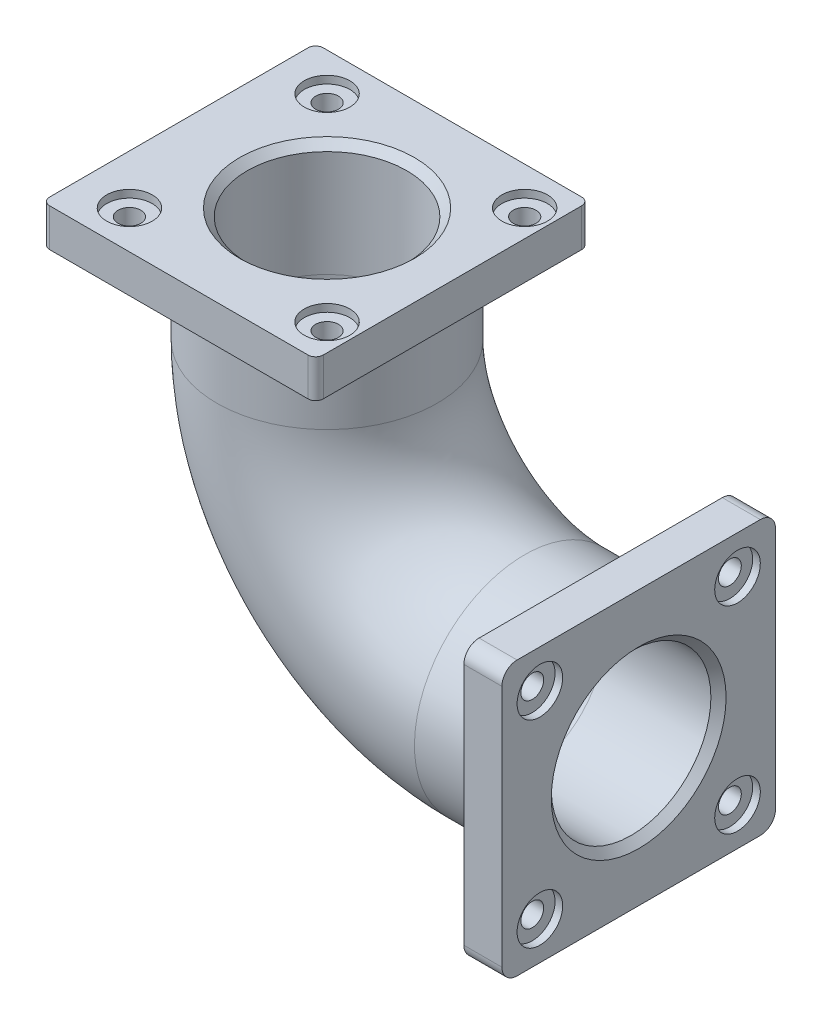
SolidWorks part; units mm, degrees
ref_plane "Front Plane" through (0, 0, 0) normal (0, 0, 1) x (1, 0, 0)
ref_plane "Top Plane" through (0, 0, 0) normal (0, 1, 0) x (1, 0, 0)
ref_plane "Right Plane" through (0, 0, 0) normal (1, 0, 0) x (0, 0, -1)
sketch "Sketch1" plane through (0, 0, 0) normal (0, 0, 1) x (1, 0, 0)
  line L0 (0, 0) -> (-150, 0)
  line L1 (-410, 260) -> (-410, 410)
  arc A0 (-150, 0) -> (-410, 260) centre (-150, 260) cw
  point P5 (0, 0)
  point P6 (0, 0)
  dimension "D2" = 260
  dimension "D1" = 150
sketch "Sketch2" plane through (0, 0, 0) normal (1, 0, 0) x (0, 0, -1)
  circle A0 centre (0, 0) radius 145
  dimension "D1" = 290
sweep "Sweep-Thin1" add profiles "Sketch2" path "Sketch1" parameters "D1"=40
sketch "Sketch3" plane through (0, 0, 0) normal (1, 0, 0) x (0, 0, -1)
  line L1 (-180, 180) -> (180, 180)
  line L2 (-180, 180) -> (-180, -180)
  line L3 (-180, -180) -> (180, -180)
  line L4 (180, 180) -> (180, -180)
  line L5 (-180, 180) -> (180, -180) construction
  line L6 (-180, -180) -> (180, 180) construction
  point P0 (0, 0)
  circle M6 centre (0, 0) radius 145
  dimension "D1" = 360
  dimension "D2" = 360
extrude "Boss-Extrude2" add sketch "Sketch3" against normal blind 50 contours L4 L1 L2 L3 M6
fillet "Fillet4" radius 20 4 edges at (-25, 180, -180) (-25, -180, 180) (-25, -180, -180) (-25, 180, 180)
sketch "Sketch4" plane through (0, 410, 0) normal (0, 1, 0) x (1, 0, 0)
  line L1 (-595.0052, 180) -> (-255.0052, 180)
  line L2 (-605.0052, 170) -> (-605.0052, -170)
  line L3 (-595.0052, -180) -> (-255.0052, -180)
  line L4 (-245.0052, 170) -> (-245.0052, -170)
  line L5 (-605.0052, 180) -> (-245.0052, -180) construction
  line L6 (-605.0052, -180) -> (-245.0052, 180) construction
  arc A0 (-595.0052, 180) -> (-605.0052, 170) centre (-595.0052, 170) ccw
  arc A1 (-255.0052, 180) -> (-245.0052, 170) centre (-255.0052, 170) cw
  arc A2 (-605.0052, -170) -> (-595.0052, -180) centre (-595.0052, -170) ccw
  arc A3 (-255.0052, -180) -> (-245.0052, -170) centre (-255.0052, -170) ccw
  point P0 (-425.0052, 0)
  point P17 (0, 0)
  point P18 (0, 0)
  point P19 (0, 0)
  point P20 (0, 0)
  point P21 (0, 0)
  point P22 (0, 0)
  point P23 (0, 0)
  point P24 (0, 0)
  point P26 (0, 0)
  point P27 (0, 0)
  dimension "D3" = 10
  dimension "D1" = 360
  dimension "D2" = 360
extrude "Boss-Extrude3" add sketch "Sketch4" against normal blind 50 contours L3 A3 L4 A1 L1 A0 L2 A2 L6
sketch "Sketch6" plane through (0, 0, 0) normal (1, 0, 0) x (0, 0, -1)
  line L1 (-130, 130) -> (130, 130)
  line L2 (-130, 130) -> (-130, -130)
  line L3 (-130, -130) -> (130, -130)
  line L4 (130, 130) -> (130, -130)
  line L5 (-130, 130) -> (130, -130) construction
  line L6 (-130, -130) -> (130, 130) construction
  circle A0 centre (-130, 130) radius 30
  point P0 (0, 0)
  dimension "D1" = 60
  dimension "D2" = 260
  dimension "D3" = 260
extrude "Cut-Extrude1" cut sketch "Sketch6" against normal blind 10 contours A0
sketch "Sketch7" plane through (-10, 0, 0) normal (1, 0, 0) x (0, 0, -1)
  circle A0 centre (-130, 130) radius 15
  dimension "D1" = 30
extrude "Cut-Extrude2" cut sketch "Sketch7" against normal up to next contours A0
pattern_circular "CirPattern1" count 4 over 360 about axis through (0, 0, 0) along (1, 0, 0) of "Cut-Extrude2", "Cut-Extrude1"
sketch "Sketch9" plane through (0, 410, 0) normal (0, 1, 0) x (1, 0, 0)
  line L1 (-540, 130) -> (-280, 130) construction
  line L2 (-540, 130) -> (-540, -130) construction
  line L3 (-540, -130) -> (-280, -130) construction
  line L4 (-280, 130) -> (-280, -130) construction
  line L5 (-540, 130) -> (-280, -130) construction
  line L6 (-540, -130) -> (-280, 130) construction
  circle A0 centre (-540, 130) radius 30
  point P0 (-410, 0)
  dimension "D3" = 60
  dimension "D1" = 260
  dimension "D2" = 260
extrude "Cut-Extrude4" cut sketch "Sketch9" against normal blind 10 contours A0
sketch "Sketch11" plane through (0, 410, 0) normal (0, 1, 0) x (1, 0, 0)
  circle A0 centre (-540, 130) radius 15
  dimension "D1" = 30
extrude "Cut-Extrude5" cut sketch "Sketch11" against normal up to next contours A0
pattern_circular "CirPattern3" count 4 over 360 about axis through (-410, 0, 0) along (0, 1, 0) of "Cut-Extrude4", "Cut-Extrude5"
chamfer "Chamfer1" distance 10 angle 45 2 edges at (0, 0, -105) (-305, 410, 0)
